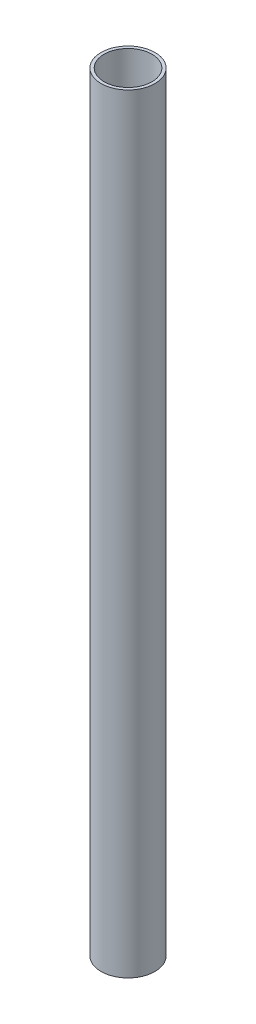
SolidWorks part; units mm, degrees
material "AISI 1020"
ref_plane "Front Plane" through (0, 0, 0) normal (0, 0, 1) x (1, 0, 0)
ref_plane "Top Plane" through (0, 0, 0) normal (0, 1, 0) x (1, 0, 0)
ref_plane "Right Plane" through (0, 0, 0) normal (1, 0, 0) x (0, 0, -1)
sketch "Sketch1" plane through (0, 0, 0) normal (0, 1, 0) x (1, 0, 0)
  circle A0 centre (13.6327, 6.0794) radius 7.0485
  circle A1 centre (13.6327, 6.0794) radius 7.9375
  dimension "D1" = 14.097
  dimension "D2" = 15.875
extrude "Boss-Extrude1" add sketch "Sketch1" along normal blind 226.52
